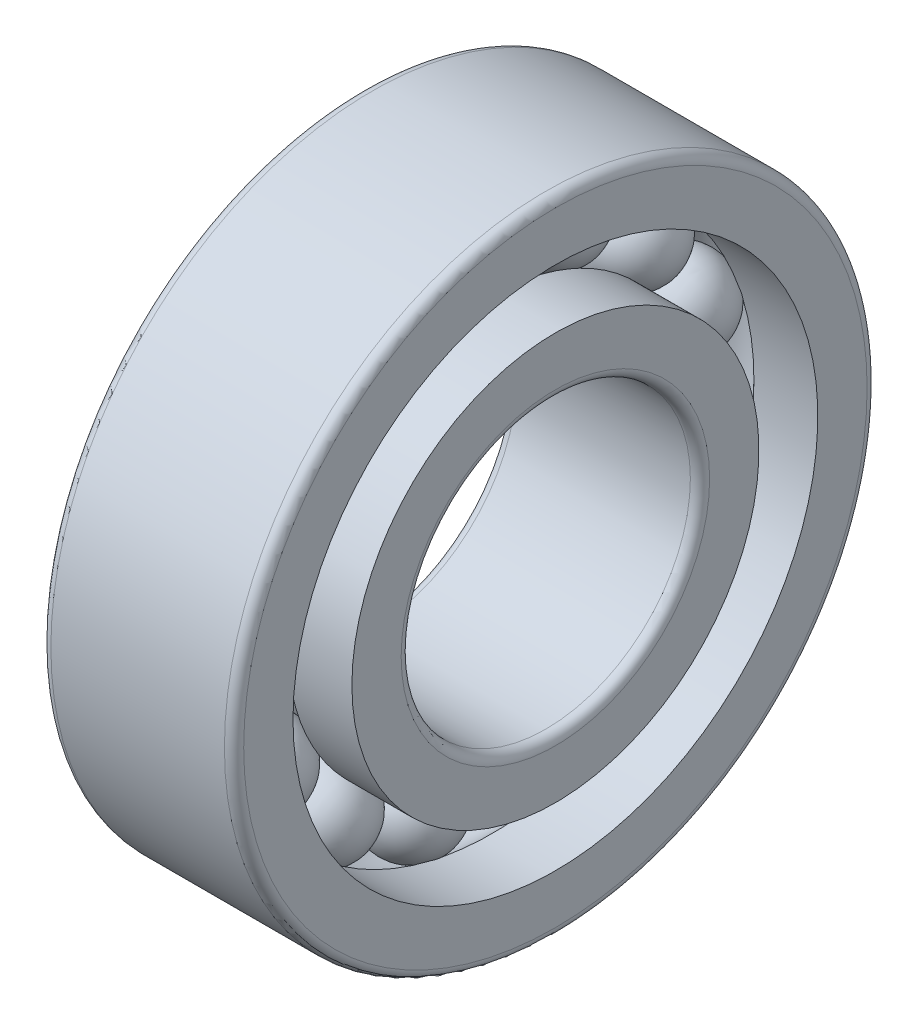
SolidWorks part; units mm, degrees
ref_plane "Front" through (0, 0, 0) normal (0, 0, 1) x (1, 0, 0)
ref_plane "Top" through (0, 0, 0) normal (0, 1, 0) x (1, 0, 0)
ref_plane "Right" through (0, 0, 0) normal (1, 0, 0) x (0, 0, -1)
other "Configuration Table"
sketch "Sketch1" plane through (0, 0, 0) normal (0, 0, 1) x (1, 0, 0)
  line L0 (-9.6833, 0) -> (9.8371, 0) construction
  line L1 (-1.375, 7.25) -> (1.375, 7.25)
  line L2 (-4.5966, 7.25) -> (4.6657, 7.25) construction
  arc A0 (1.375, 7.25) -> (-1.375, 7.25) centre (0, 7.25) ccw
  dimension "dia" = 2.75
  dimension "d0" = 14.5
revolve "Revolve1" add sketch "Sketch1" angle 360 about L2
sketch "Sketch2" plane through (0, 0, 0) normal (0, 0, 1) x (1, 0, 0)
  line L0 (-3, 6.3333) -> (-3, 4.5)
  line L1 (-3, 4.5) -> (3, 4.5)
  line L2 (3, 4.5) -> (3, 6.3333)
  line L3 (3, 6.3333) -> (1.0114, 6.3333)
  line L4 (-6.9714, 0) -> (8.1665, 0) construction
  line L5 (-6.7058, 7.25) -> (6.7058, 7.25) construction
  line L6 (-1.0114, 6.3333) -> (-3, 6.3333)
  arc A0 (-1.0114, 6.3333) -> (1.0114, 6.3333) centre (0, 7.25) ccw
  dimension "B" = 6
  dimension "B/2" = 3
  dimension "D5" = 2.73
  dimension "d" = 9
  dimension "D3" = 7.25
  dimension "D4" = 1.8333
revolve "Revolve2" add sketch "Sketch2" angle 360 about L4
sketch "Sketch3" plane through (0, 0, 0) normal (0, 0, 1) x (1, 0, 0)
  line L0 (-8.7107, 0) -> (9.1288, 0) construction
  line L1 (-3, 10) -> (3, 10)
  line L2 (-3, 10) -> (-3, 8.1667)
  line L3 (-3, 8.1667) -> (-1.0114, 8.1667)
  line L4 (3, 10) -> (3, 8.1667)
  line L5 (-7.2948, 7.25) -> (7.2948, 7.25) construction
  line L6 (1.0114, 8.1667) -> (3, 8.1667)
  arc A0 (1.0114, 8.1667) -> (-1.0114, 8.1667) centre (0, 7.25) ccw
  dimension "D1" = 2.73
  dimension "DD" = 20
  dimension "B" = 6
  dimension "D4" = 7.25
  dimension "D5" = 1.8333
  dimension "B/2" = 3
revolve "Revolve3" add sketch "Sketch3" angle 360 about L0
pattern_circular "Circular-Pattern1" count 15 over 360 about axis through (0, 0, 0) along (1, 0, 0) of "Revolve1"
fillet "Fillet1" radius 0.3 4 edges at (-3, 0, 4.5) (-3, 0, 10) (3, 0, 10) (3, 0, 4.5)
equation "\"d0@Sketch1\" = ( \"DD@Sketch3\" + \"d@Sketch2\" )  / 2"
equation "\"dia@Sketch1\" =  ( \"DD@Sketch3\" - \"d@Sketch2\" )  / 4"
equation "\"D3@Sketch2\" = ( \"DD@Sketch3\" + \"d@Sketch2\" )  / 2 / 2"
equation "\"D4@Sketch2\" = ( \"DD@Sketch3\" - \"d@Sketch2\" )  / 6"
equation "\"D5@Sketch2\" = \"dia@Sketch1\" - 0.02"
equation "\"B/2@Sketch2\" = \"B@Sketch2\" / 2"
equation "\"D4@Sketch3\" = ( \"DD@Sketch3\" + \"d@Sketch2\" )  / 2 / 2"
equation "\"D5@Sketch3\" = ( \"DD@Sketch3\" - \"d@Sketch2\" )  / 6"
equation "\"B@Sketch3\" = \"B@Sketch2\""
equation "\"B/2@Sketch3\" = \"B@Sketch3\" / 2"
equation "\"D1@Sketch3\" = \"dia@Sketch1\" - 0.02"
equation "\"m@Circular-Pattern1\" = int( 3.14159265 / atn(( \"dia@Sketch1\" / 2) / sqr(( \"DD@Sketch3\" + \"d@Sketch2\" )  / 2 * ( \"DD@Sketch3\" + \"d@Sketch2\" )  / 2/4 - ( \"dia@Sketch1\" / 2) *  ( \"dia@Sketch1\" / 2))))-1"
